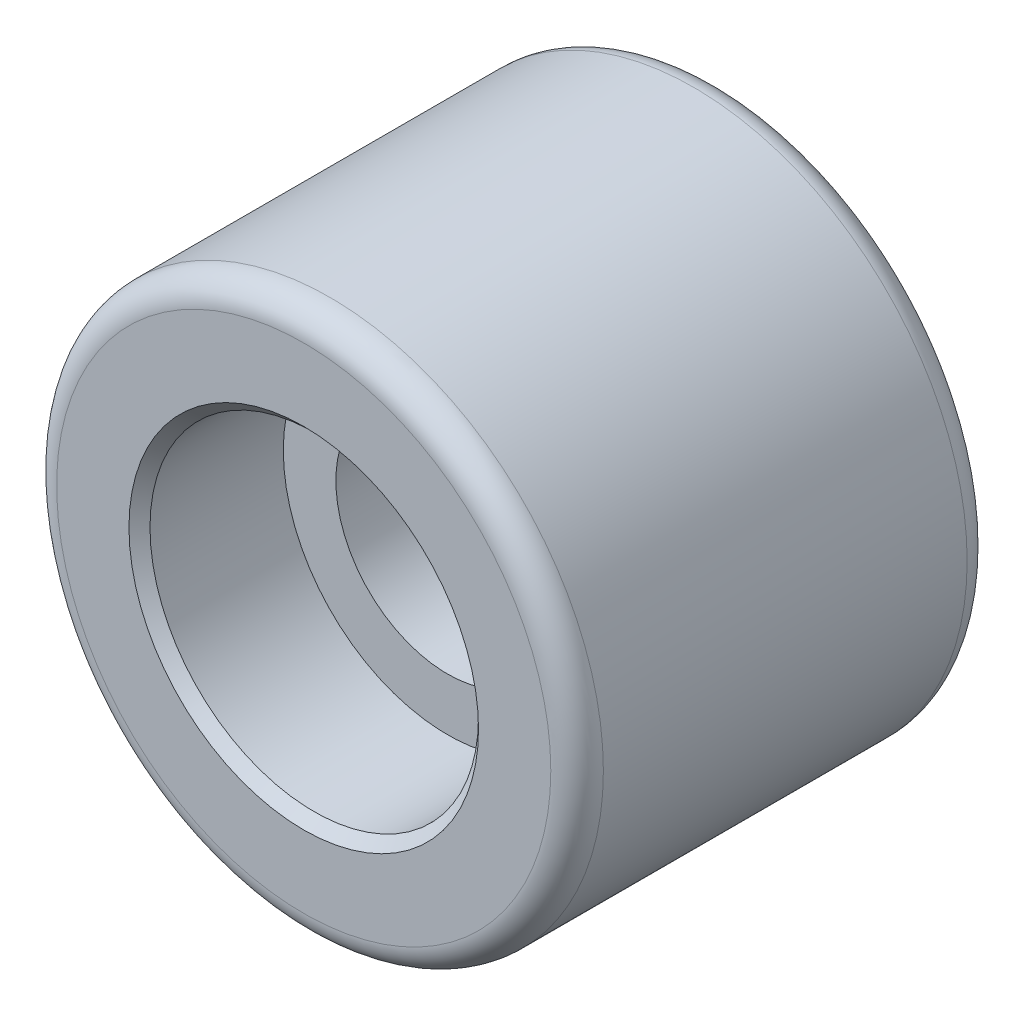
SolidWorks part; units mm, degrees
ref_plane "Front Plane" through (0, 0, 0) normal (0, 0, 1) x (1, 0, 0)
ref_plane "Top Plane" through (0, 0, 0) normal (0, 1, 0) x (1, 0, 0)
ref_plane "Right Plane" through (0, 0, 0) normal (1, 0, 0) x (0, 0, -1)
sketch "Sketch1" plane through (0, 0, 0) normal (0, 0, 1) x (1, 0, 0)
  circle A0 centre (-66.4149, -15.9298) radius 16.51
  circle A1 centre (-66.4149, -15.9298) radius 4.7625
  dimension "D1" = 33.02
  dimension "D2" = 9.525
extrude "Boss-Extrude1" add sketch "Sketch1" along normal blind 25.146
fillet "Fillet2" radius 1.5875 2 edges at (-49.9049, -15.9298, 0) (-49.9049, -15.9298, 25.146)
hole_wizard "CBORE for 1/2 Socket Shoulder Screw1" positions "Sketch3" profile "Sketch4" counterbore size "1/2" standard "ANSI Inch" end condition through all
sketch "Sketch3" plane through (0, 0, 25.146) normal (0, 0, 1) x (1, 0, 0)
  point P0 (-66.4149, -15.9298)
sketch "Sketch4" plane through (-66.4149, -15.9298, 25.146) normal (1, 0, 0) x (0, -1, 0)
  line L0 (0, 0) -> (0, 25.146)
  line L1 (0, 25.146) -> (6.7462, 25.146)
  line L3 (6.7462, 25.146) -> (6.7462, 8.6868)
  line L4 (9.9212, 8.6868) -> (6.7462, 8.6868)
  line L5 (9.9212, 8.6868) -> (9.9212, 0.635)
  line L6 (9.9212, 0.635) -> (10.5562, 0)
  line L7 (10.5562, 0) -> (0, 0)
  line L8 (-9.9212, 0.635) -> (-10.5562, 0) construction
  line L11 (0, -6.35) -> (0, 107.95) construction
  dimension "Thru Hole Dia." = 13.4925
  dimension "Thru Hole Depth" = 25.146
  dimension "C'Bore Dia." = 19.8425
  dimension "C'Bore Depth" = 8.6868
  dimension "Near C'Sink Dia." = 21.1125
  dimension "Near C'Sink Angle" = 90
